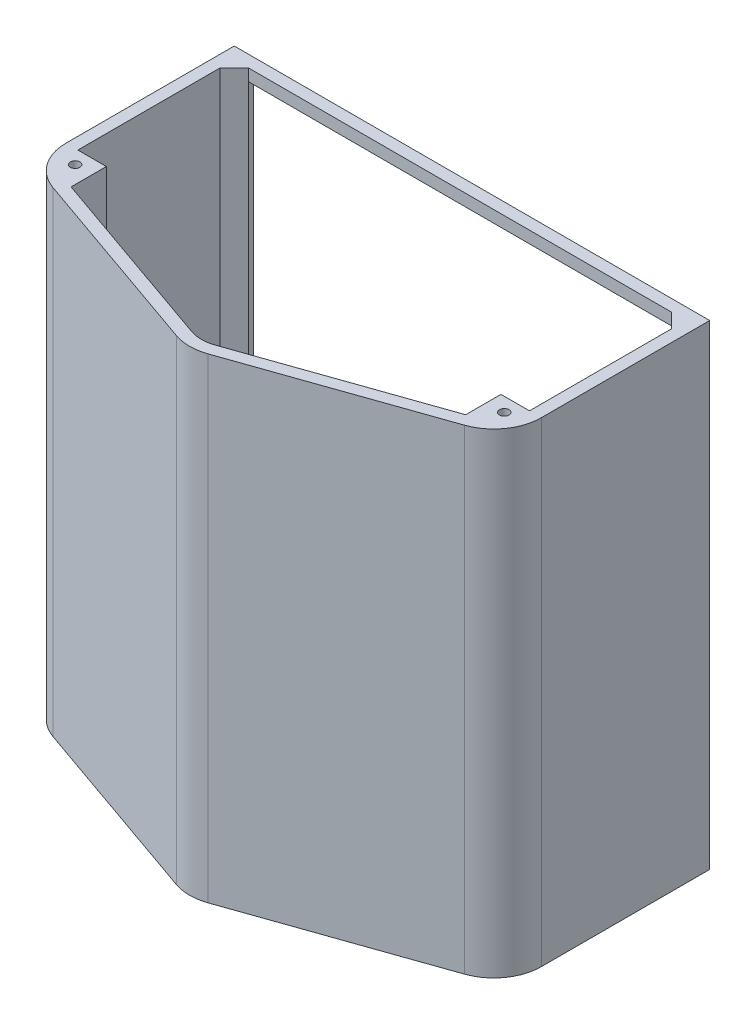
SolidWorks part; units mm, degrees
ref_plane "Front Plane" through (0, 0, 0) normal (0, 0, 1) x (1, 0, 0)
ref_plane "Top Plane" through (0, 0, 0) normal (0, 1, 0) x (1, 0, 0)
ref_plane "Right Plane" through (0, 0, 0) normal (1, 0, 0) x (0, 0, -1)
sketch "Sketch1" plane through (0, 0, 0) normal (0, 1, 0) x (1, 0, 0)
  line L0 (0, 0) -> (200, 0)
  line L1 (200, 0) -> (200, -70.8104)
  line L2 (0, 0) -> (0, -70.8104)
  line L4 (13.393, -89.6875) -> (93.393, -117.6875)
  line L5 (186.607, -89.6875) -> (106.607, -117.6875)
  arc A0 (93.393, -117.6875) -> (106.607, -117.6875) centre (100, -98.8104) ccw
  arc A1 (200, -70.8104) -> (186.607, -89.6875) centre (180, -70.8104) cw
  arc A2 (13.393, -89.6875) -> (0, -70.8104) centre (20, -70.8104) cw
  point P12 (200, -85)
  point P15 (0, -85)
  dimension "D5" = 20
  dimension "D1" = 200
  dimension "D2" = 85
  dimension "D3" = 85
extrude "Boss-Extrude1" add sketch "Sketch1" along normal blind 200 contours L2 A2 L4 A0 L5 A1 L1 L0
shell "Shell3" thickness 5
sketch "Sketch2" plane through (0, 0, 0) normal (0, 1, 0) x (1, 0, 0)
  line L0 (195, 0) -> (187.4587, 0)
  line L1 (0, 0) -> (200, 0) construction
  line L2 (189, -3) -> (189, -5)
  line L3 (5, -5) -> (195, -5) construction
  line L4 (189, -5) -> (11, -5)
  line L6 (12.3079, 0) -> (5, 0)
  line L7 (5, 0) -> (5, -3)
  line L8 (5, -3) -> (11, -3)
  line L9 (12.3079, 0) -> (187.4587, 0)
  line L10 (189, -3) -> (195, -3)
  line L11 (195, -3) -> (195, 0)
  line L12 (11, -3) -> (11, -5)
  dimension "D1" = 3
  dimension "D2" = 6
  dimension "D3" = 3
  dimension "D4" = 6
extrude "Cut-Extrude1" cut sketch "Sketch2" along normal blind 195
sketch "Sketch3" plane through (0, 0, 0) normal (0, 1, 0) x (1, 0, 0)
  line L0 (5, -5) -> (5, -11)
  line L1 (5, -5) -> (5, -70.8104) construction
  line L2 (5, -11) -> (11, -5)
  line L3 (5, -5) -> (195, -5) construction
  line L4 (11, -5) -> (5, -5)
  line L5 (195, -5) -> (195, -11)
  line L6 (195, -5) -> (195, -70.8104) construction
  line L7 (195, -11) -> (189, -5)
  line L8 (189, -5) -> (195, -5)
  dimension "D1" = 6
  dimension "D2" = 6
  dimension "D3" = 6
  dimension "D4" = 6
extrude "Boss-Extrude2" add sketch "Sketch3" along normal blind 200
sketch "Sketch4" plane through (0, 0, 0) normal (0, 1, 0) x (1, 0, 0)
  line L0 (5, -70.8104) -> (17, -70.8104)
  line L1 (17, -70.8104) -> (17, -85.6526)
  line L2 (15.0447, -84.9683) -> (95.0447, -112.9683) construction
  line L3 (13.393, -89.6875) -> (0, -70.8104)
  line L4 (5, -70.8104) -> (0, -70.8104)
  line L5 (195, -70.8104) -> (183, -70.8104)
  line L8 (186.607, -89.6875) -> (200, -70.8104)
  line L9 (200, -70.8104) -> (195, -70.8104)
  line L10 (17, -85.6526) -> (13.393, -89.6875)
  line L11 (183, -70.8104) -> (183, -85.6526)
  line L12 (184.9553, -84.9683) -> (104.9553, -112.9683) construction
  line L13 (183, -85.6526) -> (186.607, -89.6875)
  dimension "D1" = 12
  dimension "D2" = 14.8422
  dimension "D3" = 12
  dimension "D4" = 14.8422
extrude "Boss-Extrude3" add sketch "Sketch4" along normal blind 200
sketch "Sketch5" plane through (0, 0, 0) normal (0, 1, 0) x (1, 0, 0)
  line L2 (9.7435, -76.6773) -> (11, -78.2315)
  line L4 (195, -70.8104) -> (183, -70.8104)
  line L6 (190.2565, -76.6773) -> (189, -78.2315)
  circle A0 centre (9.7435, -76.6773) radius 1.9986
  circle A1 centre (190.2565, -76.6773) radius 1.9986
  dimension "D2" = 1.9986
  dimension "D1" = 1.9986
extrude "Cut-Extrude2" cut sketch "Sketch5" along normal blind 210 contours A1 | A0
sketch "Sketch6" plane through (0, 0, 0) normal (0, -1, 0) x (-1, 0, 0)
  line L0 (-100, -118.8104) -> (-100, 0)
  line L1 (-195, 0) -> (-5, 0) construction
  arc A0 (-106.607, -117.6875) -> (-93.393, -117.6875) centre (-100, -98.8104) ccw construction
